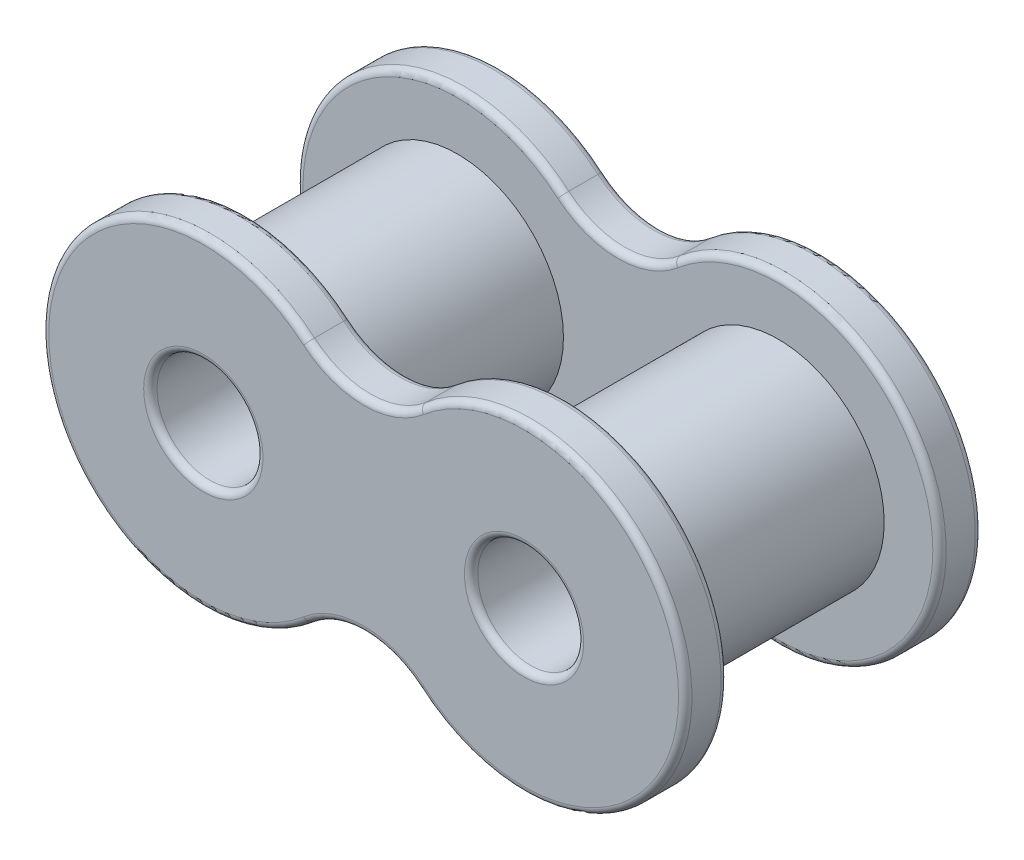
SolidWorks part; units mm, degrees
other "Câmera1"
ref_plane "Plano frontal" through (0, 0, 0) normal (0, 0, 1) x (1, 0, 0)
ref_plane "Plano superior" through (0, 0, 0) normal (0, 1, 0) x (1, 0, 0)
ref_plane "Plano direito" through (0, 0, 0) normal (1, 0, 0) x (0, 0, -1)
sketch "Esboço1" plane through (0, 0, 0) normal (0, 0, 1) x (1, 0, 0)
  line L0 (0, 6.1557) -> (0, 0) construction
  line L1 (0, 0) -> (-6, 0) construction
  circle A0 centre (-6, 0) radius 1.9812
  arc A1 (-2.0856, 4.59) -> (-2.0856, -4.59) centre (-6, 0) ccw
  circle A2 centre (6, 0) radius 1.9812
  arc A3 (2.0856, 4.59) -> (2.0856, -4.59) centre (6, 0) cw
  arc A4 (-2.0856, 4.59) -> (2.0856, 4.59) centre (0, 7.0356) ccw
  arc A5 (-2.0856, -4.59) -> (2.0856, -4.59) centre (0, -7.0356) cw
  dimension "D1" = 3.9624
  dimension "D2" = 12.065
  dimension "D4" = 3.2141
  dimension "D3" = 6
extrude "Ressalto-extrusão1" add sketch "Esboço1" along normal blind 1.5875
fillet "Filete1" radius 0.25 8 edges at (0, -3.8215, 0) (-12.0325, 0, 0) (0, 3.8215, 0) (0, 3.8215, 1.5875) (12.0325, 0, 1.5875) (0, -3.8215, 1.5875) (12.0325, 0, 0) (-12.0325, 0, 1.5875)
sketch "Esboço2" plane through (0, 0, 1.5875) normal (0, 0, 1) x (1, 0, 0)
  circle A0 centre (-6, 0) radius 3.9624
  circle A1 centre (-6, 0) radius 1.9812
  dimension "D1" = 7.9248
extrude "Ressalto-extrusão2" add sketch "Esboço2" along normal blind 7.9248
mirror "Espelhar1" about plane through (0, 0, 0) normal (1, 0, 0) of "Ressalto-extrusão2"
ref_plane "Plano1" through (0, 0, 5.5499) normal (0, 0, 1) x (1, 0, 0)
mirror "Espelhar2" about plane through (0, 0, 5.5499) normal (0, 0, 1) of "Filete1", "Ressalto-extrusão1"
fillet "Filete2" radius 0.25 4 edges at (4.0188, 0, 11.0998) (-4.0188, 0, 11.0998) (4.0188, 0, 0) (-4.0188, 0, 0)
